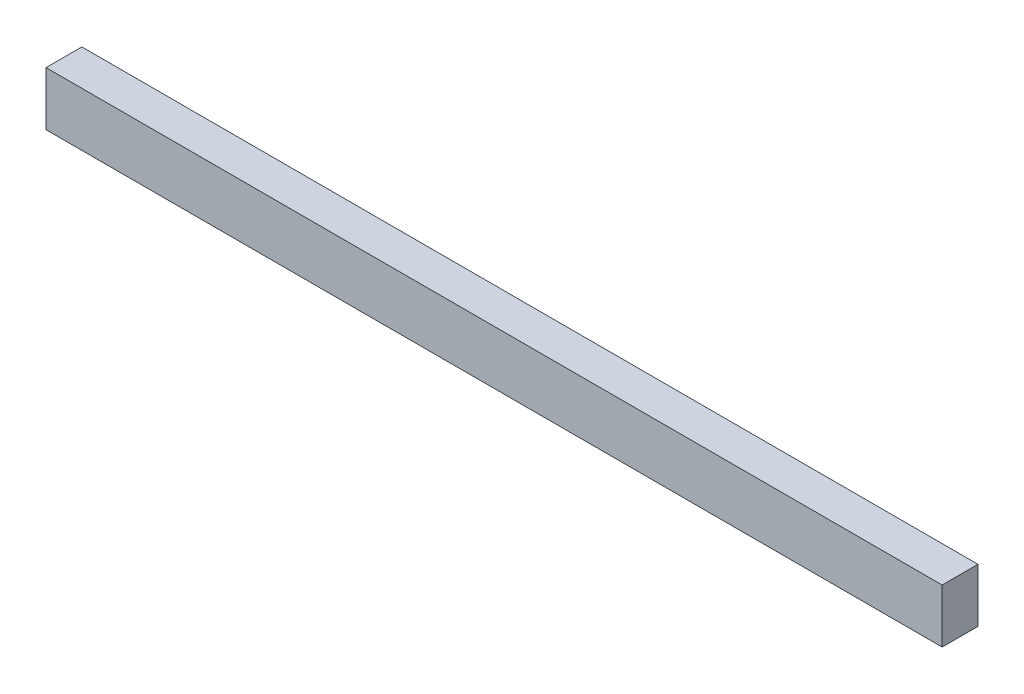
SolidWorks part; units mm, degrees
ref_plane "Alzado" through (0, 0, 0) normal (0, 0, 1) x (1, 0, 0)
ref_plane "Planta" through (0, 0, 0) normal (0, 1, 0) x (1, 0, 0)
ref_plane "Vista lateral" through (0, 0, 0) normal (1, 0, 0) x (0, 0, -1)
sketch "Croquis2" plane through (0, 0, 0) normal (0, 0, 1) x (1, 0, 0)
  line L1 (635, -38.1) -> (-635, -38.1)
  line L2 (635, -38.1) -> (635, 38.1)
  line L3 (635, 38.1) -> (-635, 38.1)
  line L4 (-635, -38.1) -> (-635, 38.1)
  line L5 (635, -38.1) -> (-635, 38.1) construction
  line L6 (635, 38.1) -> (-635, -38.1) construction
  point P0 (0, 0)
  dimension "D1" = 1270
  dimension "D2" = 76.2
extrude "Saliente-Extruir1" add sketch "Croquis2" along normal blind 50.8
